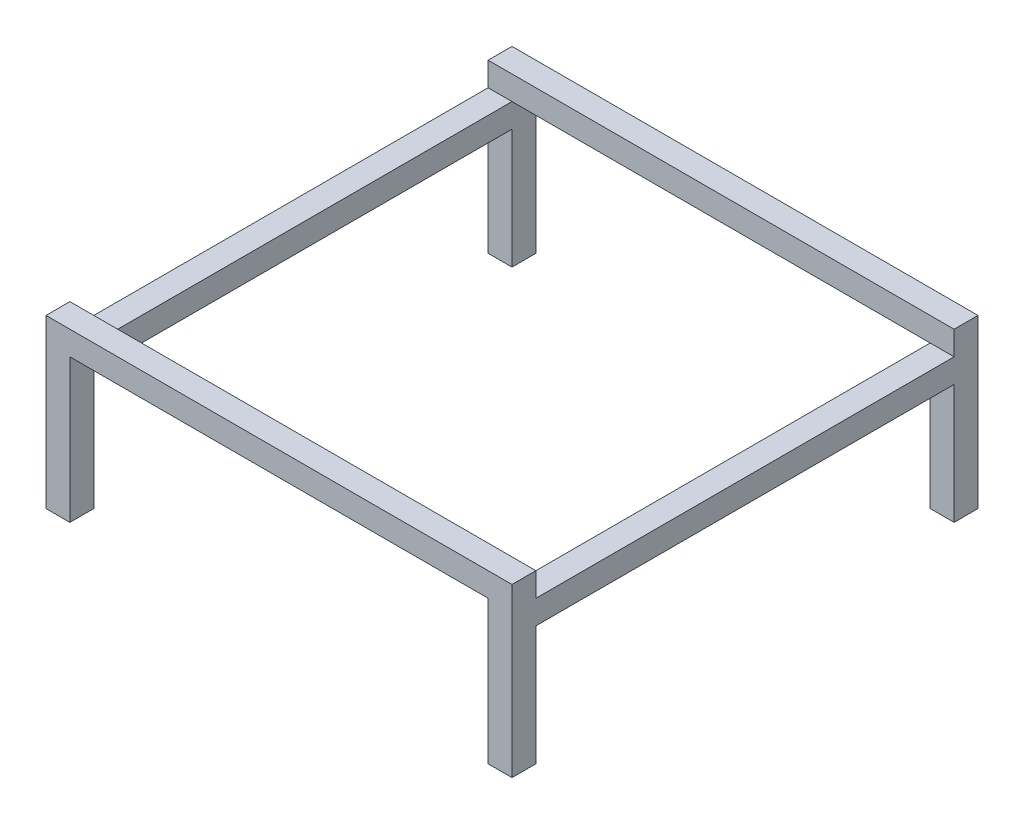
SolidWorks part; units mm, degrees
ref_plane "Front Plane" through (0, 0, 0) normal (0, 0, 1) x (1, 0, 0)
ref_plane "Top Plane" through (0, 0, 0) normal (0, 1, 0) x (1, 0, 0)
ref_plane "Right Plane" through (0, 0, 0) normal (1, 0, 0) x (0, 0, -1)
sketch "Sketch1" plane through (0, 0, 0) normal (0, 1, 0) x (1, 0, 0)
  line L0 (-195, -195) -> (-195, 195)
  line L1 (175, -175) -> (-175, -175)
  line L2 (175, -175) -> (175, 175)
  line L3 (175, 175) -> (-175, 175)
  line L4 (-175, -175) -> (-175, 175)
  line L5 (175, -175) -> (-175, 175) construction
  line L6 (175, 175) -> (-175, -175) construction
  line L7 (195, 195) -> (-195, 195)
  line L8 (195, -195) -> (195, 195)
  line L9 (195, -195) -> (-195, -195)
  point P0 (0, 0)
  dimension "D1" = 350
  dimension "D2" = 350
  dimension "D3" = 20
extrude "Boss-Extrude1" add sketch "Sketch1" along normal blind 20
sketch "Sketch2" plane through (0, 0, 0) normal (0, -1, 0) x (1, 0, 0)
  line L0 (0, 0) -> (0, -175) construction
  line L1 (-195, 195) -> (-175, 195)
  line L2 (-195, 195) -> (-195, 175)
  line L3 (-195, 175) -> (-175, 175)
  line L4 (-175, 195) -> (-175, 175)
  line L5 (175, -175) -> (-175, -175) construction
  line L6 (175, 195) -> (175, 175)
  line L7 (195, 175) -> (175, 175)
  line L8 (195, 195) -> (195, 175)
  line L9 (195, 195) -> (175, 195)
  line L10 (0, 0) -> (175, 0) construction
  line L11 (175, 175) -> (175, -175) construction
  line L12 (195, -195) -> (175, -195)
  line L13 (195, -195) -> (195, -175)
  line L14 (195, -175) -> (175, -175)
  line L15 (175, -195) -> (175, -175)
  line L16 (-175, -195) -> (-175, -175)
  line L17 (-195, -175) -> (-175, -175)
  line L18 (-195, -195) -> (-195, -175)
  line L19 (-195, -195) -> (-175, -195)
extrude "Boss-Extrude2" add sketch "Sketch2" along normal blind 100
sketch "Sketch4" plane through (0, 20, 0) normal (0, 1, 0) x (1, 0, 0)
  line L0 (195, -195) -> (195, 195) construction
  line L1 (-195, -195) -> (195, -195)
  line L2 (-195, -195) -> (-195, -175)
  line L3 (-195, -175) -> (195, -175)
  line L4 (195, -195) -> (195, -175)
  line L5 (175, 175) -> (-175, 175) construction
  line L6 (-195, 195) -> (195, 195)
  line L7 (-195, 195) -> (-195, 175)
  line L8 (-195, 175) -> (195, 175)
  line L9 (195, 195) -> (195, 175)
  line L10 (-175, -175) -> (175, -175) construction
extrude "Boss-Extrude3" add sketch "Sketch4" along normal blind 20
sketch "Sketch5" plane through (0, 0, 195) normal (0, 0, 1) x (1, 0, 0)
  line L0 (175, -100) -> (175, 0) construction
  line L1 (-175, 0) -> (175, 0)
  line L2 (-175, 0) -> (-175, 20)
  line L3 (-175, 20) -> (175, 20)
  line L4 (175, 0) -> (175, 20)
  dimension "D1" = 20
extrude "Cut-Extrude1" cut sketch "Sketch5" against normal through all both and the other way through all
